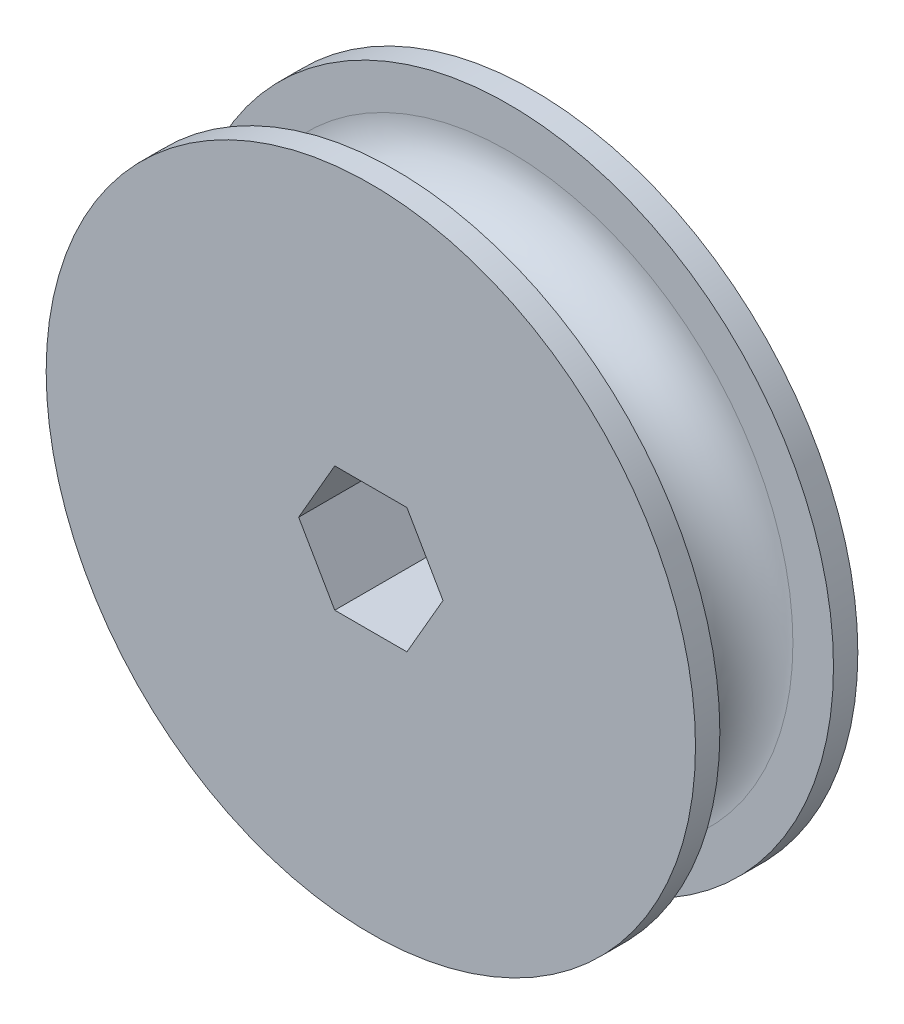
SolidWorks part; units mm, degrees
ref_plane "Front Plane" through (0, 0, 0) normal (0, 0, 1) x (1, 0, 0)
ref_plane "Top Plane" through (0, 0, 0) normal (0, 1, 0) x (1, 0, 0)
ref_plane "Right Plane" through (0, 0, 0) normal (1, 0, 0) x (0, 0, -1)
sketch "Sketch1" plane through (0, 0, 0) normal (0, 0, 1) x (1, 0, 0)
  circle A0 centre (0, 0) radius 25.4
  dimension "D1" = 50.8
extrude "Boss-Extrude1" add sketch "Sketch1" along normal mid plane 12.7
sketch "Sketch3" plane through (0, 0, 0) normal (0, 1, 0) x (1, 0, 0)
  line L0 (-25.4, 6.35) -> (-25.4, -6.35) construction
  line L1 (-25.4, 4.445) -> (-25.4, -4.445)
  line L2 (-22.225, 4.445) -> (-25.4, 4.445)
  line L3 (-22.225, -4.445) -> (-25.4, -4.445)
  arc A0 (-22.225, -4.445) -> (-22.225, 4.445) centre (-22.225, 0) ccw
  dimension "D1" = 8.89
  dimension "D2" = 3.175
ref_axis "Axis1" through (0, 0, 17.1197) along (0, 0, -1)
revolve "Cut-Revolve1" cut sketch "Sketch3" angle 360 about axis through (0, 0, 17.1197) along (0, 0, -1)
sketch "Sketch4" plane through (0, 0, -6.35) normal (0, 0, -1) x (-1, 0, 0)
  line L0 (5.6459, 0) -> (2.823, 4.8895)
  line L1 (2.823, 4.8895) -> (-2.823, 4.8895)
  line L2 (-2.823, 4.8895) -> (-5.6459, 0)
  line L3 (-5.6459, 0) -> (-2.823, -4.8895)
  line L4 (-2.823, -4.8895) -> (2.823, -4.8895)
  line L5 (2.823, -4.8895) -> (5.6459, 0)
  point P2 (0, 4.8895)
  dimension "D1" = 9.779
  dimension "D2" = 9.779
  dimension "D3" = 9.779
  dimension "D4" = 4.8895
  dimension "D5" = 120
extrude "Cut-Extrude1" cut sketch "Sketch4" against normal through all
